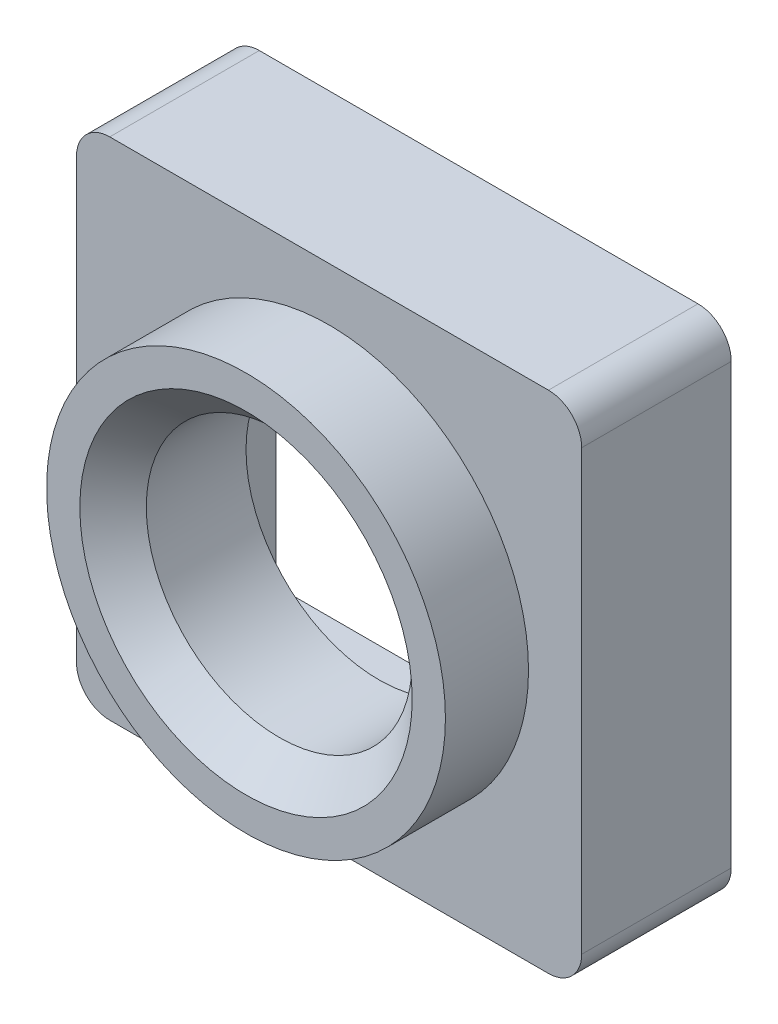
SolidWorks part; units mm, degrees
ref_plane "Спереди" through (0, 0, 0) normal (0, 0, 1) x (1, 0, 0)
ref_plane "Сверху" through (0, 0, 0) normal (0, 1, 0) x (1, 0, 0)
ref_plane "Справа" through (0, 0, 0) normal (1, 0, 0) x (0, 0, -1)
sketch "Sketch1" plane through (0, 0, 0) normal (0, 0, 1) x (1, 0, 0)
  circle A0 centre (0, 0) radius 6
  circle A1 centre (0, 0) radius 4
  dimension "D1" = 12
  dimension "D2" = 8
extrude "Extrude1" add sketch "Sketch1" along normal blind 2.5
chamfer "Chamfer1" distance 1 angle 45 1 edges at (4, 0, 2.5)
sketch "Sketch2" plane through (0, 0, 0) normal (0, 0, -1) x (-1, 0, 0)
  line L0 (-6.1, 6.1) -> (-6.1, -6.1) construction
  line L1 (-7.6, -7.6) -> (7.6, -7.6)
  line L2 (-7.6, -7.6) -> (-7.6, 7.6)
  line L3 (-7.6, 7.6) -> (7.6, 7.6)
  line L4 (7.6, -7.6) -> (7.6, 7.6)
  line L5 (-7.6, -7.6) -> (7.6, 7.6) construction
  line L6 (-7.6, 7.6) -> (7.6, -7.6) construction
  line L7 (-6.1, 6.1) -> (6.1, 6.1) construction
  circle A0 centre (0, 0) radius 4 construction
  circle A1 centre (0, 0) radius 4
  dimension "D1" = 12.2
  dimension "D2" = 1.5
extrude "Extrude3" add sketch "Sketch2" along normal blind 1.5
sketch "Sketch3" plane through (0, 0, -1.5) normal (0, 0, -1) x (-1, 0, 0)
  line L0 (6.1, 6.1) -> (-6.1, 6.1)
  line L1 (-6.1, 6.1) -> (-6.1, -6.1)
  line L2 (-6.1, -6.1) -> (6.1, -6.1)
  line L3 (6.1, -6.1) -> (6.1, 6.1)
  line L4 (7.6, -7.6) -> (7.6, 7.6)
  line L5 (7.6, 7.6) -> (-7.6, 7.6)
  line L6 (-7.6, 7.6) -> (-7.6, -7.6)
  line L7 (-7.6, -7.6) -> (7.6, -7.6)
  line L8 (7.6, -7.6) -> (7.6, 7.6)
  line L9 (7.6, 7.6) -> (-7.6, 7.6)
  line L10 (-7.6, 7.6) -> (-7.6, -7.6)
  line L11 (-7.6, -7.6) -> (7.6, -7.6)
  dimension "D2" = 12.2
  dimension "D1" = 0
extrude "Extrude4" add sketch "Sketch3" along normal blind 3
fillet "Fillet1" radius 1 4 edges at (-7.6, -7.6, -2.25) (7.6, -7.6, -2.25) (7.6, 7.6, -2.25) (-7.6, 7.6, -2.25)
fillet "Fillet2" radius 0.5 4 edges at (-6.1, -6.1, -3) (6.1, -6.1, -3) (6.1, 6.1, -3) (-6.1, 6.1, -3)
